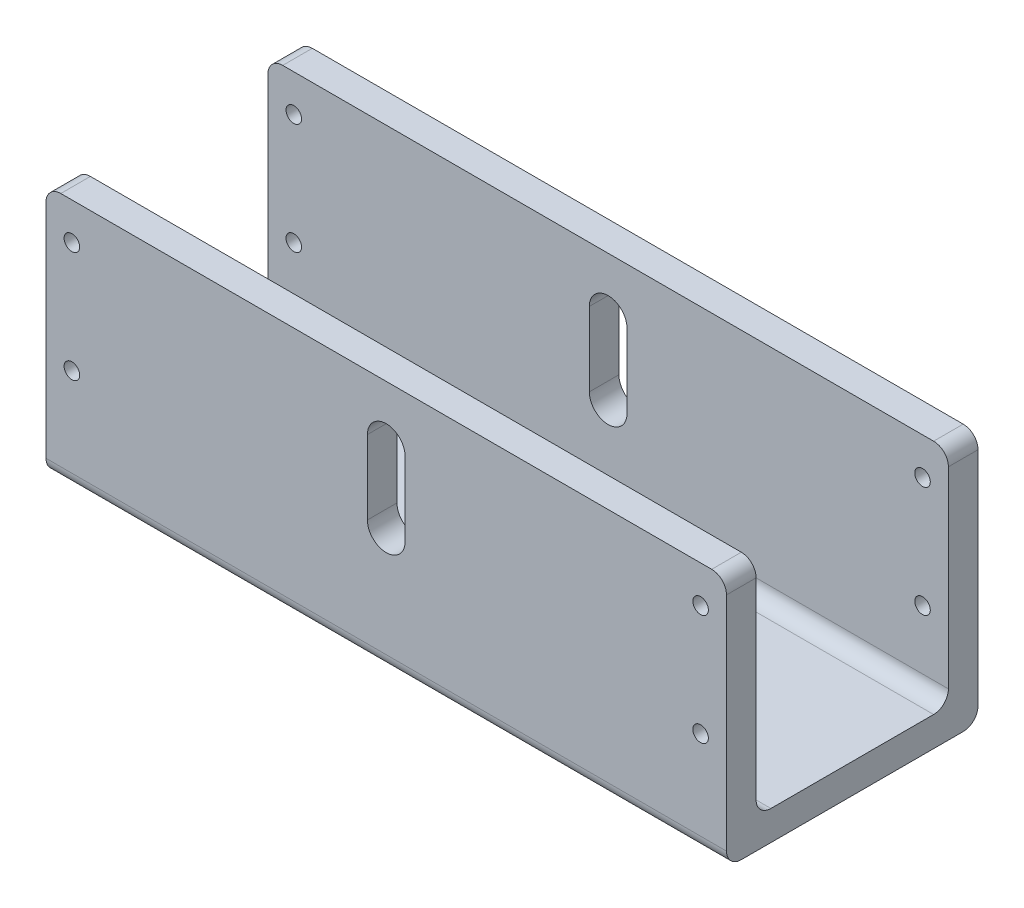
SolidWorks part; units mm, degrees
ref_plane "前视基准面" through (0, 0, 0) normal (0, 0, 1) x (1, 0, 0)
ref_plane "上视基准面" through (0, 0, 0) normal (0, 1, 0) x (1, 0, 0)
ref_plane "右视基准面" through (0, 0, 0) normal (1, 0, 0) x (0, 0, -1)
sketch "草图1" plane through (0, 0, 0) normal (0, 0, 1) x (1, 0, 0)
  line L1 (0, 0) -> (92, 0)
  line L2 (0, 0) -> (0, -30)
  line L3 (0, -30) -> (92, -30)
  line L4 (92, 0) -> (92, -30)
  line L5 (43.45, -17.5) -> (43.45, -7.5)
  line L6 (48.55, -17.5) -> (48.55, -7.5)
  circle A0 centre (3.5, -5) radius 1.05
  circle A1 centre (3.5, -20) radius 1.05
  circle A2 centre (88.5, -5) radius 1.05
  circle A3 centre (88.5, -20) radius 1.05
  arc A7 (43.45, -17.5) -> (48.55, -17.5) centre (46, -17.5) ccw
  arc A8 (48.55, -7.5) -> (43.45, -7.5) centre (46, -7.5) ccw
  point P17 (46.1066, -12.5)
  point P22 (46, 0)
  dimension "D3" = 2
  dimension "D5" = 7.5
  dimension "D6" = 5
  dimension "D1" = 92
  dimension "D2" = 30
  dimension "D7" = 43.45
  dimension "D8" = 5.1
  dimension "D4" = 2
extrude "凸台-拉伸1" add sketch "草图1" along normal blind 4
sketch "草图4" plane through (0, -30, 0) normal (0, -1, 0) x (-1, 0, 0)
  line L1 (0, 0) -> (-92, 0)
  line L2 (0, 0) -> (0, -30)
  line L3 (0, -30) -> (-92, -30)
  line L4 (-92, 0) -> (-92, -30)
  dimension "D1" = 92
  dimension "D2" = 30
extrude "凸台-拉伸4" add sketch "草图4" along normal blind 4
sketch "草图5" plane through (0, 0, 30) normal (0, 0, 1) x (1, 0, 0)
  line L1 (0, -34) -> (92, -34)
  line L2 (0, -34) -> (0, 0)
  line L3 (0, 0) -> (92, 0)
  line L4 (92, -34) -> (92, 0)
  circle A0 centre (3.5, -5) radius 1.05
  circle A1 centre (3.5, -20) radius 1.05
  circle A2 centre (88.5, -20) radius 1.05
  circle A3 centre (88.5, -5) radius 1.05
extrude "凸台-拉伸5" add sketch "草图5" along normal blind 4
fillet "圆角4" radius 2 8 edges at (46, -30, 30) (0, 0, 32) (92, 0, 32) (92, 0, 2) (0, 0, 2) (46, -34, 0) (46, -34, 34) (46, -30, 4)
sketch "草图7" plane through (0, 0, 0) normal (0, 0, -1) x (-1, 0, 0)
  line L0 (-46, -17.5) -> (-46, -7.5) construction
  line L1 (-48.55, -17.5) -> (-48.55, -7.5)
  line L2 (-43.45, -17.5) -> (-43.45, -7.5)
  arc A0 (-48.55, -17.5) -> (-43.45, -17.5) centre (-46, -17.5) ccw
  arc A1 (-43.45, -7.5) -> (-48.55, -7.5) centre (-46, -7.5) ccw
  point P4 (-46, -12.5)
extrude "切除-拉伸1" cut sketch "草图7" against normal blind 45
sketch "草图8" plane through (0, -34, 0) normal (0, -1, 0) x (-1, 0, 0)
  line L0 (-92, 0) -> (0, 0) construction
  line L1 (0, -32) -> (0, -2) construction
  circle A2 centre (-46, -16.5) radius 2.55
  dimension "D1" = 16.5
  dimension "D2" = 46
extrude "切除-拉伸2" cut sketch "草图8" against normal blind 5
